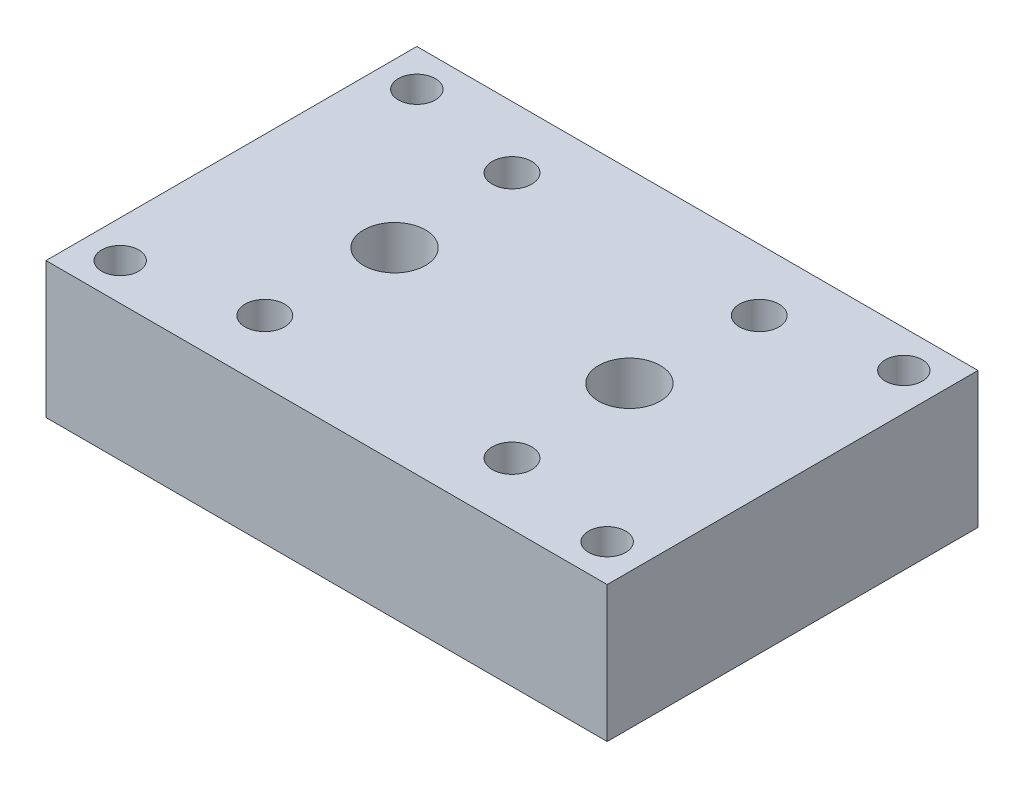
SolidWorks part; units mm, degrees
ref_plane "Front Plane" through (0, 0, 0) normal (0, 0, 1) x (1, 0, 0)
ref_plane "Top Plane" through (0, 0, 0) normal (0, 1, 0) x (1, 0, 0)
ref_plane "Right Plane" through (0, 0, 0) normal (1, 0, 0) x (0, 0, -1)
sketch "Sketch1" plane through (0, 0, 0) normal (0, 1, 0) x (1, 0, 0)
  line L1 (-22.7, -15) -> (22.7, -15)
  line L2 (-22.7, -15) -> (-22.7, 15)
  line L3 (-22.7, 15) -> (22.7, 15)
  line L4 (22.7, -15) -> (22.7, 15)
  line L5 (-22.7, -15) -> (22.7, 15) construction
  line L6 (-22.7, 15) -> (22.7, -15) construction
  point P0 (0, 0)
  dimension "D1" = 45.4
  dimension "D2" = 30
extrude "Boss-Extrude1" add sketch "Sketch1" along normal blind 11
sketch "Sketch2" plane through (0, 11, 0) normal (0, 1, 0) x (1, 0, 0)
  line L0 (-22.7, 15) -> (-22.7, -15) construction
  line L1 (22.7, -15) -> (22.7, 15) construction
  line L2 (22.7, 15) -> (-22.7, 15) construction
  circle A0 centre (-9.5, 0) radius 2.5
  circle A1 centre (9.5, 0) radius 2.5
  dimension "D1" = 5
  dimension "D2" = 5
  dimension "D3" = 13.2
  dimension "D4" = 13.2
  dimension "D5" = 15
  dimension "D6" = 15
extrude "Cut-Extrude1" cut sketch "Sketch2" against normal through all
hole_wizard "Ø3.0mm Dowel Hole1" positions "Sketch3" profile "Sketch4" hole size "Ø3.0" standard "ANSI Metric" end condition through all
sketch "Sketch3" plane through (0, 11, 0) normal (0, 1, 0) x (1, 0, 0)
  line L0 (22.7, 15) -> (-22.7, 15) construction
  line L1 (-22.7, 15) -> (-22.7, -15) construction
  point P0 (-10, 10)
  point P5 (10, 10)
  point P6 (10, -10)
  point P7 (-10, -10)
  dimension "D3" = 5
  dimension "D4" = 12.7
  dimension "D1" = 2
  dimension "D2" = 2
sketch "Sketch4" plane through (-10, 11, -10) normal (1, 0, 0) x (0, 0, 1)
  line L0 (0, 0) -> (0, 11)
  line L1 (0, 11) -> (1.6, 11)
  line L2 (1.6, 11) -> (1.6, 0)
  line L5 (1.6, 0) -> (0, 0)
  line L11 (0, -6.35) -> (0, 107.95) construction
  dimension "Thru Hole Dia." = 3.2
  dimension "Thru Hole Depth" = 11
sketch "Sketch5" plane through (0, 0, 0) normal (0, -1, 0) x (1, 0, 0)
  line L0 (-22.7, 15) -> (22.7, 15) construction
  line L1 (22.7, 15) -> (22.7, -15) construction
  circle A0 centre (0, -5) radius 3
  dimension "D1" = 6
  dimension "D2" = 20
  dimension "D3" = 22.7
extrude "Boss-Extrude2" add sketch "Sketch5" along normal blind 4.5
sketch "Sketch6" plane through (0, -4.5, 0) normal (0, -1, 0) x (1, 0, 0)
  circle A0 centre (0, -5) radius 1.75
  dimension "D1" = 3.5
extrude "Boss-Extrude3" add sketch "Sketch6" along normal blind 3
sketch "Sketch7" plane through (0, 11, 0) normal (0, 1, 0) x (1, 0, 0)
  line L0 (-22.7, 15) -> (-22.7, -15) construction
  line L1 (22.7, 15) -> (-22.7, 15) construction
  line L2 (22.7, -15) -> (22.7, 15) construction
  line L3 (-22.7, -15) -> (22.7, -15) construction
  circle A0 centre (-19.7, 12) radius 1.5
  circle A1 centre (19.7, 12) radius 1.5
  circle A2 centre (19.7, -12) radius 1.5
  circle A3 centre (-19.7, -12) radius 1.5
  dimension "D1" = 3
  dimension "D2" = 3
  dimension "D3" = 3
  dimension "D4" = 3
  dimension "D5" = 3
  dimension "D6" = 3
  dimension "D7" = 3
  dimension "D8" = 3
  dimension "D9" = 3
  dimension "D10" = 3
  dimension "D11" = 3
  dimension "D12" = 3
extrude "Cut-Extrude2" cut sketch "Sketch7" against normal blind 4
